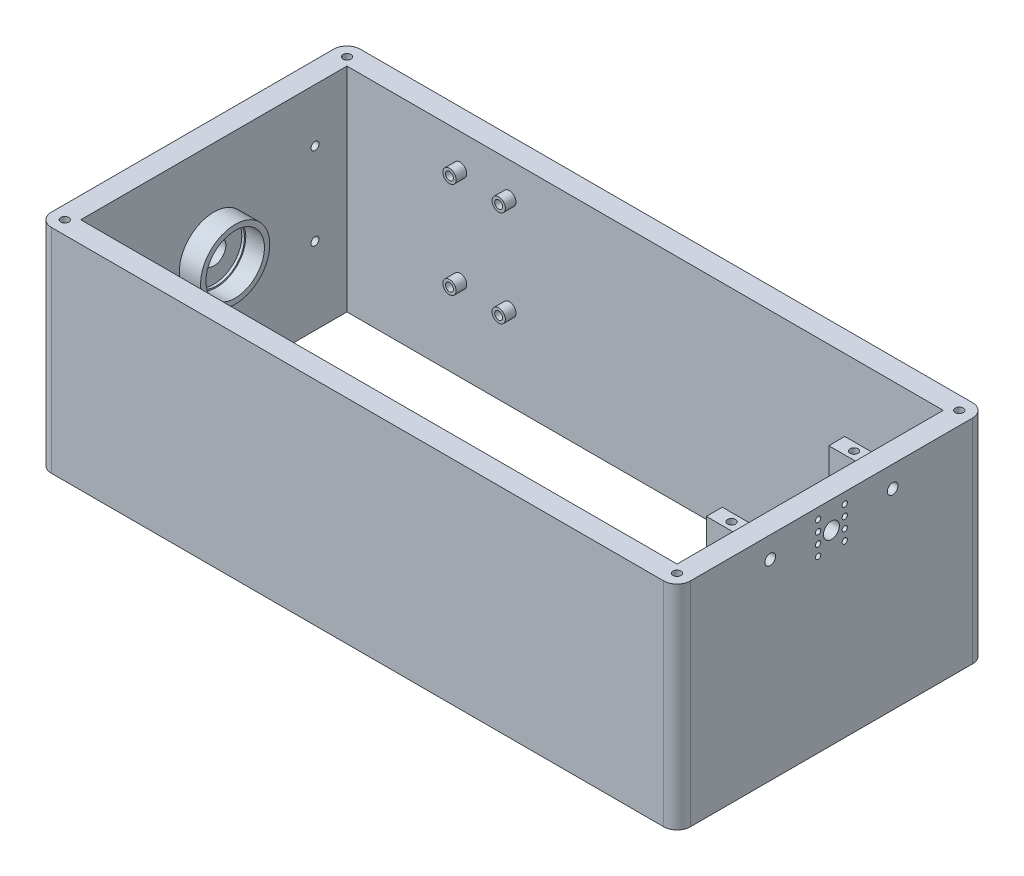
SolidWorks part; units mm, degrees
ref_plane "Front Plane" through (0, 0, 0) normal (0, 0, 1) x (1, 0, 0)
ref_plane "Top Plane" through (0, 0, 0) normal (0, 1, 0) x (1, 0, 0)
ref_plane "Right Plane" through (0, 0, 0) normal (1, 0, 0) x (0, 0, -1)
sketch "Sketch1" plane through (0, 0, 0) normal (0, 1, 0) x (1, 0, 0)
  line L1 (-120, 58) -> (120, 58)
  line L2 (-120, 58) -> (-120, -58)
  line L3 (-120, -58) -> (120, -58)
  line L4 (120, 58) -> (120, -58)
  line L5 (-120, 58) -> (120, -58) construction
  line L6 (-120, -58) -> (120, 58) construction
  point P0 (0, 0)
  dimension "D1" = 240
  dimension "D2" = 116
extrude "Boss-Extrude1" add sketch "Sketch1" along normal blind 10
sketch "Sketch2" plane through (0, 0, 0) normal (0, -1, 0) x (1, 0, 0)
  line L1 (-31.075, 31.075) -> (31.075, 31.075)
  line L2 (-31.075, 31.075) -> (-31.075, -31.075)
  line L3 (-31.075, -31.075) -> (31.075, -31.075)
  line L4 (31.075, 31.075) -> (31.075, -31.075)
  line L5 (-31.075, 31.075) -> (31.075, -31.075) construction
  line L6 (-31.075, -31.075) -> (31.075, 31.075) construction
  point P0 (0, 0)
  dimension "D1" = 62.15
  dimension "D2" = 62.15
extrude "Cut-Extrude1" [suppressed] cut sketch "Sketch2" against normal blind 2.5
sketch "Sketch3" [suppressed] plane through (0, 2.5, 0) normal (0, -1, 0) x (1, 0, 0)
  line L0 (0, 31.075) -> (0, -31.075) construction
  line L1 (31.075, 31.075) -> (-31.075, 31.075) construction
  line L2 (-31.075, -31.075) -> (31.075, -31.075) construction
  line L3 (-31.075, 0) -> (31.075, 0) construction
  line L4 (-31.075, 31.075) -> (-31.075, -31.075) construction
  line L5 (31.075, -31.075) -> (31.075, 31.075) construction
  line L6 (31.075, 31.075) -> (-31.075, 31.075) construction
  line L7 (-31.075, 31.075) -> (-31.075, -31.075) construction
  circle A0 centre (-26.075, 26.075) radius 1.5
  circle A1 centre (-26.075, -26.075) radius 1.5
  circle A2 centre (26.075, -26.075) radius 1.5
  circle A3 centre (26.075, 26.075) radius 1.5
  dimension "D1" = 3
  dimension "D3" = 5
  dimension "D2" = 5
extrude "Cut-Extrude2" [suppressed] cut sketch "Sketch3" against normal up to next
sketch "Sketch4" plane through (0, 0, 0) normal (0, -1, 0) x (1, 0, 0)
  line L0 (120, 58) -> (120, -58) construction
  line L1 (48, 7.75) -> (60, 7.75)
  line L2 (48, 7.75) -> (48, -7.75)
  line L3 (48, -7.75) -> (60, -7.75)
  line L4 (60, 7.75) -> (60, -7.75)
  line L5 (48, 7.75) -> (60, -7.75) construction
  line L6 (48, -7.75) -> (60, 7.75) construction
  point P0 (54, 0)
  dimension "D1" = 12
  dimension "D2" = 15.5
  dimension "D3" = 60
extrude "Cut-Extrude3" [suppressed] cut sketch "Sketch4" against normal blind 2.5
sketch "Sketch6" [suppressed] plane through (0, 2.5, 0) normal (0, -1, 0) x (1, 0, 0)
  line L0 (60, -7.75) -> (60, 7.75) construction
  line L1 (60, 7.75) -> (48, 7.75) construction
  line L2 (48, -7.75) -> (60, -7.75) construction
  circle A0 centre (58, 5.75) radius 1.5
  circle A1 centre (58, -5.75) radius 1.5
  dimension "D1" = 3
  dimension "D2" = 3
  dimension "D3" = 2
  dimension "D4" = 2
  dimension "D5" = 2
  dimension "D6" = 2
extrude "Cut-Extrude4" [suppressed] cut sketch "Sketch6" against normal up to next and the other way through all
sketch "Sketch7" [suppressed] plane through (0, 2.5, 0) normal (0, -1, 0) x (1, 0, 0)
  line L0 (48, -7.75) -> (60, -7.75) construction
  line L1 (48, 7.75) -> (54, 7.75)
  line L2 (48, 7.75) -> (48, -7.75)
  line L3 (48, -7.75) -> (54, -7.75)
  line L4 (54, 7.75) -> (54, -7.75)
extrude "Cut-Extrude5" [suppressed] cut sketch "Sketch7" against normal up to next
sketch "Sketch8" plane through (0, 10, 0) normal (0, 1, 0) x (1, 0, 0)
  line L1 (1.2, 26.7) -> (100, 26.7) construction
  line L2 (1.2, 26.7) -> (1.2, -26.7) construction
  line L3 (1.2, -26.7) -> (100, -26.7) construction
  line L4 (100, 26.7) -> (100, -26.7) construction
  line L5 (1.2, 26.7) -> (100, -26.7) construction
  line L6 (1.2, -26.7) -> (100, 26.7) construction
  line L11 (120, -58) -> (120, 58) construction
  line L15 (-120, -58) -> (120, -58) construction
  circle A0 centre (2.7, 24.2) radius 1.5
  circle A1 centre (9.7, -24.2) radius 1.5
  circle A2 centre (86.5, 24.2) radius 1.5
  circle A3 centre (84.5, -24.2) radius 1.5
  circle A4 centre (86.5, 24.2) radius 2.5
  circle A5 centre (84.5, -24.2) radius 2.3473
  circle A6 centre (9.7, -24.2) radius 2.5
  circle A7 centre (2.7, 24.2) radius 2.5
  point P0 (50.6, 0)
  dimension "D7" = 3
  dimension "D8" = 3
  dimension "D9" = 3
  dimension "D10" = 3
  dimension "D11" = 2.5
  dimension "D13" = 8.5
  dimension "D14" = 2.5
  dimension "D12" = 15.5
  dimension "D16" = 13.5
  dimension "D17" = 2.5
  dimension "D18" = 5
  dimension "D19" = 5
  dimension "D20" = 5
  dimension "D1" = 98.8
  dimension "D2" = 53.4
  dimension "D3" = 20
  dimension "D4" = 58
  dimension "D15" = 2.5
extrude "Boss-Extrude2" [suppressed] add sketch "Sketch8" along normal blind 15
sketch "Sketch9" [suppressed] plane through (0, 10, 0) normal (0, 1, 0) x (1, 0, 0)
  line L0 (-0.3, 58) -> (-0.3, -58) construction
  line L1 (-25.6, 47) -> (-4.3, 47) construction
  line L2 (-25.6, 47) -> (-25.6, 8.5) construction
  line L3 (-25.6, 8.5) -> (-4.3, 8.5) construction
  line L4 (-4.3, 47) -> (-4.3, 8.5) construction
  line L5 (-25.6, 47) -> (-4.3, 8.5) construction
  line L6 (-25.6, 8.5) -> (-4.3, 47) construction
  line L7 (-53.1, 47) -> (-29.6, 47) construction
  line L8 (-53.1, 47) -> (-53.1, 5) construction
  line L9 (-53.1, 5) -> (-29.6, 5) construction
  line L10 (-29.6, 47) -> (-29.6, 5) construction
  line L11 (-53.1, 47) -> (-29.6, 5) construction
  line L12 (-53.1, 5) -> (-29.6, 47) construction
  line L13 (120, 58) -> (-120, 58) construction
  line L14 (-120, -58) -> (120, -58) construction
  line L15 (-76.2, -9.5) -> (-54.9, -9.5) construction
  line L16 (-103.7, -9) -> (-80.2, -9) construction
  line L17 (-17.7, -47) -> (-17.7, -48)
  line L18 (-21.7, -23.8) -> (-4.3, -23.8)
  line L19 (-21.7, -23.8) -> (-21.7, -47)
  line L20 (-21.7, -47) -> (-17.7, -47)
  line L21 (-4.3, -23.8) -> (-4.3, -47)
  line L22 (-21.7, -23.8) -> (-4.3, -47) construction
  line L23 (-21.7, -47) -> (-4.3, -23.8) construction
  line L24 (-22.7, -22.8) -> (-3.3, -22.8)
  line L25 (-22.7, -22.8) -> (-22.7, -48)
  line L26 (-22.7, -48) -> (-17.7, -48)
  line L27 (-3.3, -22.8) -> (-3.3, -48)
  line L28 (-22.7, -22.8) -> (-3.3, -48) construction
  line L29 (-22.7, -48) -> (-3.3, -22.8) construction
  line L30 (-8.3, -47) -> (-8.3, -48)
  line L31 (-8.3, -47) -> (-4.3, -47)
  line L32 (-8.3, -48) -> (-3.3, -48)
  line L33 (-24.7, -58) -> (-24.7, -13.4898) construction
  line L34 (-26.7, -48) -> (-46.1, -22.8) construction
  line L35 (-26.7, -22.8) -> (-46.1, -48) construction
  line L36 (-27.7, -47) -> (-45.1, -23.8) construction
  line L37 (-27.7, -23.8) -> (-45.1, -47) construction
  line L38 (-41.1, -48) -> (-46.1, -48)
  line L39 (-41.1, -47) -> (-45.1, -47)
  line L40 (-41.1, -47) -> (-41.1, -48)
  line L41 (-46.1, -22.8) -> (-46.1, -48)
  line L42 (-26.7, -48) -> (-31.7, -48)
  line L43 (-26.7, -22.8) -> (-26.7, -48)
  line L44 (-26.7, -22.8) -> (-46.1, -22.8)
  line L45 (-45.1, -23.8) -> (-45.1, -47)
  line L46 (-27.7, -47) -> (-31.7, -47)
  line L47 (-27.7, -23.8) -> (-27.7, -47)
  line L48 (-27.7, -23.8) -> (-45.1, -23.8)
  line L49 (-31.7, -47) -> (-31.7, -48)
  line L50 (-48.1, -58) -> (-48.1, -12.5562) construction
  line L51 (-31.46, 43.383) -> (-31.46, 8.617)
  line L52 (-50.24, 42.383) -> (-32.46, 42.383)
  line L53 (-50.24, 42.383) -> (-50.24, 9.617)
  line L54 (-50.24, 9.617) -> (-32.46, 9.617)
  line L67 (31.45, 58) -> (31.45, -58) construction
  line L102 (-32.46, 42.383) -> (-32.46, 9.617)
  line L103 (-50.24, 42.383) -> (-32.46, 9.617) construction
  line L104 (-50.24, 9.617) -> (-32.46, 42.383) construction
  line L105 (-51.24, 8.617) -> (-31.46, 8.617)
  line L106 (-51.24, 43.383) -> (-51.24, 8.617)
  line L107 (-51.24, 43.383) -> (-31.46, 43.383)
  circle A0 centre (2.7, 24.2) radius 1.5 construction
  circle A1 centre (-5.8, 42.5) radius 1.5
  circle A2 centre (-5.8, 15.8) radius 1.5
  circle A3 centre (-24.1, 15.8) radius 1.5
  circle A4 centre (-24.1, 15.8) radius 2.5
  circle A5 centre (-5.8, 15.8) radius 2.5
  circle A6 centre (-5.8, 42.5) radius 2.5
  circle A7 centre (-50.6, 44.5) radius 1.5 construction
  circle A8 centre (-32.1, 44.5) radius 1.5 construction
  circle A9 centre (-32.1, 7.5) radius 1.5 construction
  circle A10 centre (-50.6, 7.5) radius 1.5 construction
  circle A11 centre (-50.6, 7.5) radius 2.5 construction
  circle A12 centre (-32.1, 7.5) radius 2.5 construction
  circle A13 centre (-32.1, 44.5) radius 2.5 construction
  circle A14 centre (-50.6, 44.5) radius 2.5 construction
  point P0 (-14.95, 27.75)
  point P5 (-41.35, 26)
  point P20 (-13, -35.4)
  point P27 (-13, -35.4)
  point P50 (-36.4, -35.4)
  point P53 (-41.35, 26)
  dimension "D23" = 3
  dimension "D24" = 3
  dimension "D25" = 3
  dimension "D28" = 5
  dimension "D29" = 5
  dimension "D30" = 5
  dimension "D31" = 3
  dimension "D32" = 3
  dimension "D33" = 3
  dimension "D34" = 3
  dimension "D43" = 5
  dimension "D44" = 5
  dimension "D45" = 5
  dimension "D46" = 5
  dimension "D1" = 38.5
  dimension "D2" = 21.3
  dimension "D3" = 3
  dimension "D4" = 4
  dimension "D5" = 18
  dimension "D6" = 42
  dimension "D7" = 23.5
  dimension "D8" = 4
  dimension "D9" = 11
  dimension "D10" = 14
  dimension "D11" = 17.4
  dimension "D12" = 23.2
  dimension "D13" = 11
  dimension "D14" = 4
  dimension "D15" = 25.2
  dimension "D16" = 19.4
  dimension "D17" = 4
  dimension "D18" = 4
  dimension "D19" = 2
  dimension "D20" = 2
  dimension "D22" = 4.5
  dimension "D26" = 7.3
  dimension "D27" = 7.3
  dimension "D35" = 2.5
  dimension "D36" = 2.5
  dimension "D37" = 2.5
  dimension "D38" = 2.5
  dimension "D39" = 2.5
  dimension "D40" = 2.5
  dimension "D41" = 2.5
  dimension "D42" = 2.5
  dimension "D47" = 32.766
  dimension "D48" = 17.78
  dimension "D49" = 1
extrude "Boss-Extrude3" [suppressed] add sketch "Sketch9" along normal blind 4
sketch "Sketch10" plane through (0, 10, 0) normal (0, 1, 0) x (1, 0, 0)
  line L0 (-112, 50) -> (112, 50)
  line L1 (-120, 58) -> (120, 58)
  line L2 (-120, 58) -> (-120, -58)
  line L3 (-120, -58) -> (120, -58)
  line L4 (120, 58) -> (120, -58)
  line L5 (-120, 58) -> (120, -58) construction
  line L6 (-120, -58) -> (120, 58) construction
  line L7 (112, 50) -> (112, -50)
  line L8 (-112, -50) -> (112, -50)
  line L9 (-112, 50) -> (-112, -50)
  point P0 (0, 0)
  dimension "D1" = 8
extrude "Boss-Extrude4" add sketch "Sketch10" along normal blind 80
sketch "Sketch11" plane through (112, 0, 0) normal (-1, 0, 0) x (0, 0, 1)
  line L0 (-50, 90) -> (-50, 10) construction
  line L1 (-37, 82.5) -> (23, 82.5) construction
  line L2 (-37, 82.5) -> (-37, 17.5) construction
  line L3 (-37, 17.5) -> (23, 17.5) construction
  line L4 (23, 82.5) -> (23, 17.5) construction
  line L5 (-37, 82.5) -> (23, 17.5) construction
  line L6 (-37, 17.5) -> (23, 82.5) construction
  line L7 (-27.9, 70.9) -> (13.9, 70.9) construction
  line L8 (-27.9, 70.9) -> (-27.9, 29.1) construction
  line L9 (-27.9, 29.1) -> (13.9, 29.1) construction
  line L10 (13.9, 70.9) -> (13.9, 29.1) construction
  line L11 (-27.9, 70.9) -> (13.9, 29.1) construction
  line L12 (-27.9, 29.1) -> (13.9, 70.9) construction
  line L15 (50, 90) -> (-50, 90) construction
  circle A0 centre (-22.9, 65.9) radius 1.5
  circle A1 centre (8.9, 65.9) radius 1.5
  circle A2 centre (8.9, 34.1) radius 1.5
  circle A3 centre (-22.9, 34.1) radius 1.5
  circle A4 centre (-7, 67.5) radius 4.5
  point P0 (-7, 50)
  point P6 (-7, 50)
  dimension "D5" = 3
  dimension "D6" = 3
  dimension "D8" = 3
  dimension "D7" = 3
  dimension "D19" = 9
  dimension "D1" = 65
  dimension "D2" = 60
  dimension "D3" = 41.8
  dimension "D4" = 41.8
  dimension "D10" = 5
  dimension "D11" = 5
  dimension "D12" = 5
  dimension "D13" = 5
  dimension "D14" = 5
  dimension "D15" = 5
  dimension "D16" = 5
  dimension "D17" = 43
  dimension "D18" = 40
  dimension "D20" = 15
  dimension "D21" = 30
  dimension "D9" = 5
extrude "Cut-Extrude6" [suppressed] cut sketch "Sketch11" against normal up to next contours A1 | A3 | A2 | A0
sketch "Sketch13" [suppressed] plane through (120, 0, 0) normal (1, 0, 0) x (0, 0, -1)
  circle A0 centre (-8.9, 65.9) radius 3
  circle A1 centre (22.9, 65.9) radius 3
  circle A2 centre (22.9, 34.1) radius 3
  circle A3 centre (-8.9, 34.1) radius 3
  dimension "D1" = 6
  dimension "D2" = 6
  dimension "D3" = 6
  dimension "D4" = 6
extrude "Cut-Extrude7" [suppressed] cut sketch "Sketch13" against normal blind 4
sketch "Sketch24" plane through (-112, 0, 0) normal (1, 0, 0) x (0, 0, -1)
  line L0 (50, 10) -> (-50, 10) construction
  line L1 (-43, 34) -> (43, 34) construction
  line L2 (-43, 34) -> (-43, 75) construction
  line L3 (-43, 75) -> (43, 75) construction
  line L4 (43, 34) -> (43, 75) construction
  line L5 (-43, 34) -> (43, 75) construction
  line L6 (-43, 75) -> (43, 34) construction
  line L7 (50, 90) -> (-50, 90) construction
  line L8 (0, 75) -> (0, 34) construction
  circle A0 centre (-38, 70) radius 1.5
  circle A1 centre (-38, 39) radius 1.5
  circle A2 centre (38, 39) radius 1.5
  circle A3 centre (38, 70) radius 1.5
  point P0 (0, 54.5)
  point P9 (0, 10)
  dimension "D4" = 3
  dimension "D5" = 3
  dimension "D6" = 5
  dimension "D7" = 5
  dimension "D8" = 5
  dimension "D9" = 5
  dimension "D1" = 86
  dimension "D2" = 41
  dimension "D3" = 15
extrude "Cut-Extrude14" cut sketch "Sketch24" against normal up to next
sketch "Sketch14" plane through (-112, 0, 0) normal (1, 0, 0) x (0, 0, -1)
  circle A0 centre (0, 54.5) radius 13
  circle A2 centre (0, 54.5) radius 11
  dimension "D1" = 26
  dimension "D2" = 22
  dimension "D3" = 0
extrude "Boss-Extrude6" add sketch "Sketch14" along normal blind 8
sketch "Sketch16" plane through (-112, 0, 0) normal (1, 0, 0) x (0, 0, -1)
  circle A0 centre (0, 54.5) radius 10.5
  circle A1 centre (0, 54.5) radius 11
  dimension "D1" = 21
  dimension "D2" = 22
extrude "Boss-Extrude7" add sketch "Sketch16" along normal blind 1
sketch "Sketch18" plane through (0, 0, -50) normal (0, 0, 1) x (1, 0, 0)
  line L0 (-60.25, 80) -> (-60.25, 38) construction
  line L1 (-72, 80) -> (-48.5, 80) construction
  line L2 (-72, 80) -> (-72, 38) construction
  line L3 (-72, 38) -> (-48.5, 38) construction
  line L4 (-48.5, 80) -> (-48.5, 38) construction
  line L5 (-72, 80) -> (-48.5, 38) construction
  line L6 (-72, 38) -> (-48.5, 80) construction
  line L7 (-72, 59.4256) -> (-48.5, 59.4256) construction
  line L8 (112, 90) -> (-112, 90) construction
  line L9 (-112, 90) -> (-112, 10) construction
  circle A0 centre (-69.5, 77.5) radius 1.5
  circle A1 centre (-69.5, 77.5) radius 2.5
  circle A2 centre (-69.5, 41.3512) radius 1.5
  circle A3 centre (-69.5, 41.3512) radius 2.5
  circle A4 centre (-51, 41.3512) radius 2.5
  circle A5 centre (-51, 41.3512) radius 1.5
  circle A6 centre (-51, 77.5) radius 2.5
  circle A7 centre (-51, 77.5) radius 1.5
  point P0 (-60.25, 59)
  dimension "D3" = 3
  dimension "D4" = 5
  dimension "D5" = 2.5
  dimension "D6" = 2.5
  dimension "D1" = 42
  dimension "D2" = 23.5
  dimension "D7" = 10
  dimension "D8" = 40
sketch "Sketch17" plane through (-112, 0, 0) normal (1, 0, 0) x (0, 0, -1)
  circle A0 centre (0, 54.5) radius 4.5
  dimension "D1" = 9
extrude "Cut-Extrude9" cut sketch "Sketch17" against normal up to next
extrude "Boss-Extrude8" add sketch "Sketch18" along normal blind 4
fillet "Fillet1" radius 5 8 edges at (120, 45, -58) (-120, 45, -58) (0, 0, -58) (-120, 0, 0) (0, 0, 58) (-120, 45, 58) (120, 0, 0) (120, 45, 58)
sketch "Sketch19" plane through (0, 90, 0) normal (0, 1, 0) x (1, 0, 0)
  circle A3 centre (115, 53) radius 1.5
  circle A4 centre (-115, 53) radius 1.5
  circle A5 centre (-115, -53) radius 1.5
  circle A6 centre (115, -53) radius 1.5
  dimension "D1" = 3
  dimension "D2" = 3
  dimension "D3" = 3
  dimension "D4" = 3
extrude "Cut-Extrude10" cut sketch "Sketch19" against normal up to next
sketch "Sketch20" plane through (120, 0, 0) normal (1, 0, 0) x (0, 0, -1)
  line L0 (0, 90) -> (0, 0) construction
  line L1 (-53, 90) -> (53, 90) construction
  circle A0 centre (-23, 82) radius 2
  circle A1 centre (23, 82) radius 2
  dimension "D1" = 23
  dimension "D2" = 4
  dimension "D3" = 8
extrude "Cut-Extrude11" cut sketch "Sketch20" against normal up to next
sketch "Sketch21" plane through (112, 0, 0) normal (-1, 0, 0) x (0, 0, 1)
  line L1 (-26, 87) -> (-20, 87)
  line L2 (-26, 87) -> (-26, 77)
  line L3 (-26, 77) -> (-20, 77)
  line L4 (-20, 87) -> (-20, 77)
  line L5 (-26, 87) -> (-20, 77) construction
  line L6 (-26, 77) -> (-20, 87) construction
  line L7 (20, 87) -> (26, 87)
  line L8 (20, 87) -> (20, 77)
  line L9 (20, 77) -> (26, 77)
  line L10 (26, 87) -> (26, 77)
  line L11 (20, 87) -> (26, 77) construction
  line L12 (20, 77) -> (26, 87) construction
  circle A0 centre (23, 82) radius 2
  circle A1 centre (-23, 82) radius 2
  point P0 (-23, 82)
  point P6 (23, 82)
  dimension "D5" = 4
  dimension "D6" = 4
  dimension "D1" = 6
  dimension "D2" = 6
  dimension "D3" = 10
  dimension "D4" = 10
extrude "Boss-Extrude9" add sketch "Sketch21" along normal blind 13
sketch "Sketch22" plane through (0, 87, 0) normal (0, 1, 0) x (1, 0, 0)
  line L0 (99, -26) -> (99, -20) construction
  line L1 (99, -20) -> (112, -20) construction
  line L2 (99, 20) -> (99, 26) construction
  line L3 (99, 26) -> (112, 26) construction
  circle A0 centre (105.5, -23) radius 1.5
  circle A1 centre (105.5, 23) radius 1.5
  dimension "D1" = 3
  dimension "D2" = 6.5
  dimension "D3" = 3
  dimension "D4" = 3
  dimension "D5" = 6.5
  dimension "D6" = 3
extrude "Cut-Extrude12" cut sketch "Sketch22" against normal up to next
sketch "Sketch23" plane through (120, 0, 0) normal (1, 0, 0) x (0, 0, -1)
  line L0 (0, 90) -> (0, 5) construction
  line L1 (-53, 90) -> (53, 90) construction
  line L2 (-53, 5) -> (53, 5) construction
  line L3 (-9.0972, 80) -> (9.0972, 80) construction
  circle A0 centre (5, 78) radius 1
  circle A1 centre (-5, 78) radius 1
  circle A2 centre (5, 74) radius 1
  circle A3 centre (-5, 74) radius 1
  circle A4 centre (-5, 86) radius 1
  circle A5 centre (5, 86) radius 1
  circle A6 centre (-5, 82) radius 1
  circle A7 centre (5, 82) radius 1
  circle A8 centre (0, 80) radius 3
  point P24 (0, 80)
  dimension "D1" = 2
  dimension "D2" = 2
  dimension "D3" = 5
  dimension "D4" = 5
  dimension "D5" = 12
  dimension "D6" = 12
  dimension "D7" = 2
  dimension "D8" = 2
  dimension "D9" = 5
  dimension "D10" = 5
  dimension "D11" = 4
  dimension "D12" = 4
  dimension "D13" = 2
  dimension "D14" = 6
extrude "Cut-Extrude13" cut sketch "Sketch23" against normal up to next
sketch "Sketch32" plane through (-120, 0, 0) normal (-1, 0, 0) x (0, 0, 1)
  line L0 (58, 90) -> (58, 5) construction
  line L1 (-58, 0) -> (58, 0)
  line L2 (-58, 0) -> (-58, 10)
  line L3 (-58, 10) -> (58, 10)
  line L4 (58, 0) -> (58, 10)
  dimension "D1" = 10
extrude "Cut-Extrude15" cut sketch "Sketch32" against normal up to next
equation "\"D2@Sketch2\"=\"D1@Sketch2\""
equation "\"D15@Sketch9\"=\"D12@Sketch9\"+2"
equation "\"D16@Sketch9\"=\"D11@Sketch9\"+2"
equation "\"D17@Sketch11\"=86/2"
equation "\"D18@Sketch11\"=80/2"
